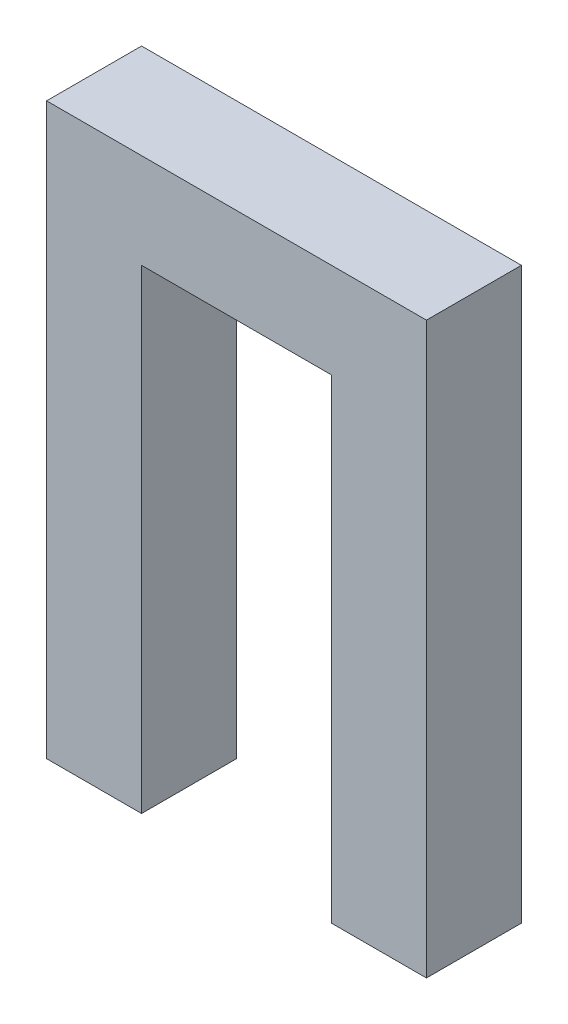
SolidWorks part; units mm, degrees
ref_plane "Ön Düzlem" through (0, 0, 0) normal (0, 0, 1) x (1, 0, 0)
ref_plane "Üst Düzlem" through (0, 0, 0) normal (0, 1, 0) x (1, 0, 0)
ref_plane "Sağ Düzlem" through (0, 0, 0) normal (1, 0, 0) x (0, 0, -1)
sketch "Çizim1" plane through (0, 0, 0) normal (0, 0, 1) x (1, 0, 0)
  line L0 (0, 0) -> (0, 50)
  line L1 (0, 50) -> (20, 50)
  line L2 (20, 50) -> (20, 0)
  line L3 (20, 0) -> (30, 0)
  line L4 (30, 0) -> (30, 60)
  line L5 (30, 60) -> (-10, 60)
  line L6 (-10, 60) -> (-10, 0)
  line L7 (-10, 0) -> (0, 0)
  line L8 (0, 0) -> (0.0834, 0.422)
  dimension "D1" = 20
  dimension "D2" = 10
  dimension "D3" = 10
  dimension "D4" = 10
  dimension "D5" = 50
extrude "Yükseklik-Ekstrüzyon1" add sketch "Çizim1" along normal blind 10 contours L6 L7 L0 L1 L2 L3 L4 L5
